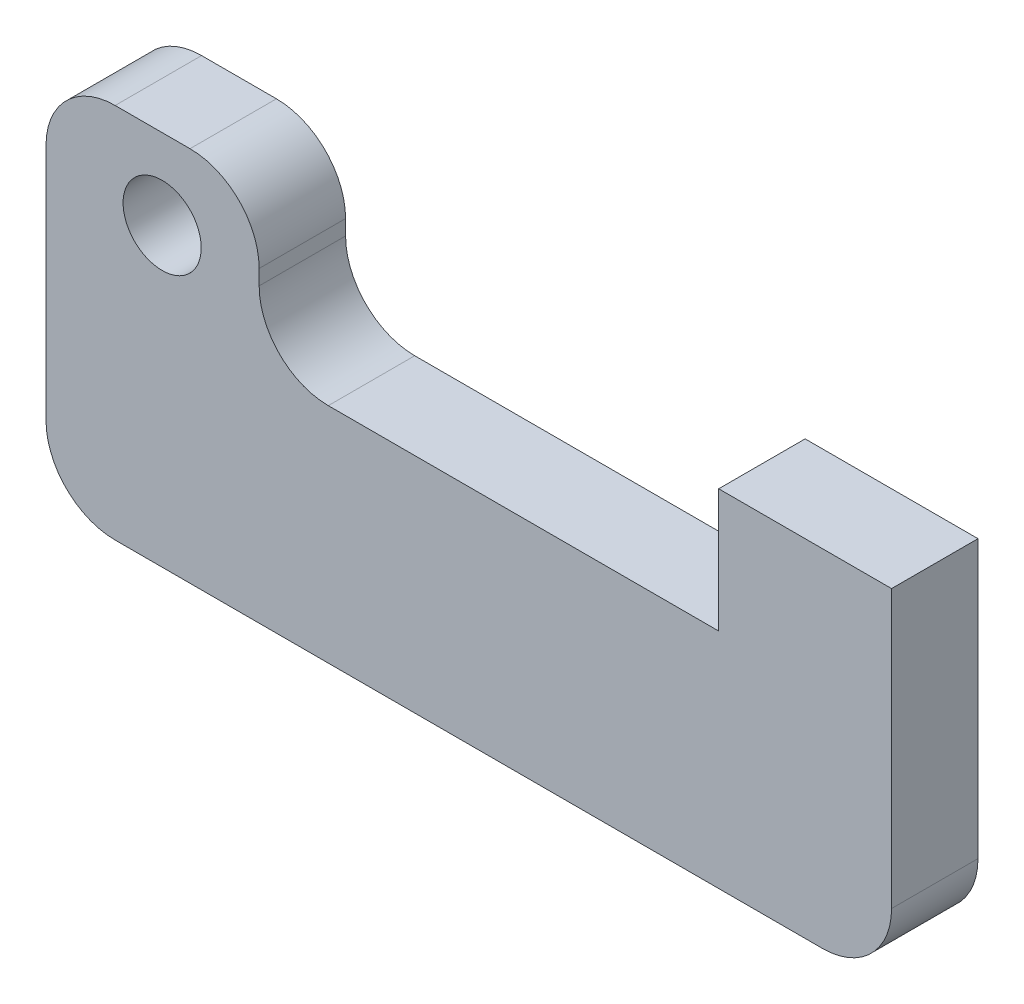
SolidWorks part; units mm, degrees
ref_plane "Front Plane" through (0, 0, 0) normal (0, 0, 1) x (1, 0, 0)
ref_plane "Top Plane" through (0, 0, 0) normal (0, 1, 0) x (1, 0, 0)
ref_plane "Right Plane" through (0, 0, 0) normal (1, 0, 0) x (0, 0, -1)
sketch "Sketch1" plane through (0, 0, 0) normal (0, 0, 1) x (1, 0, 0)
  line L0 (-195.4727, -32.9198) -> (-195.4727, 4.3392) construction
  line L1 (-133.35, 0) -> (-146.05, 0)
  line L2 (-133.35, 0) -> (-133.35, -6.35)
  line L4 (-146.05, 0) -> (-146.05, -6.35)
  line L6 (-133.35, -6.35) -> (-133.35, -25.4365)
  line L7 (-133.35, -25.4365) -> (-146.05, -25.4365)
  line L8 (-146.05, -6.35) -> (-146.05, -9.0519)
  line L9 (-146.05, -25.4365) -> (-195.4727, -25.4365)
  line L11 (-146.05, -9.0519) -> (-179.8124, -9.0519)
  line L12 (-195.4727, -25.4365) -> (-195.4727, -16.6784)
  line L15 (-195.4727, -16.6784) -> (-195.4727, 2.2161)
  line L16 (-195.4727, 2.2161) -> (-179.8124, 2.2161)
  line L17 (-179.8124, -9.0519) -> (-179.8124, 2.2161)
  arc A0 (-177.4067, -2.8416) -> (-196.4727, -3.7) centre (-186.8954, -4.254) ccw construction
  circle A1 centre (-186.9397, -3.6858) radius 2.8702
extrude "Boss-Extrude1" add sketch "Sketch1" along normal blind 6.35
fillet "Fillet1" radius 5.08 5 edges at (-133.35, -25.4365, 3.175) (-195.4727, -25.4365, 3.175) (-179.8124, -9.0519, 3.175) (-179.8124, 2.2161, 3.175) (-195.4727, 2.2161, 3.175)
